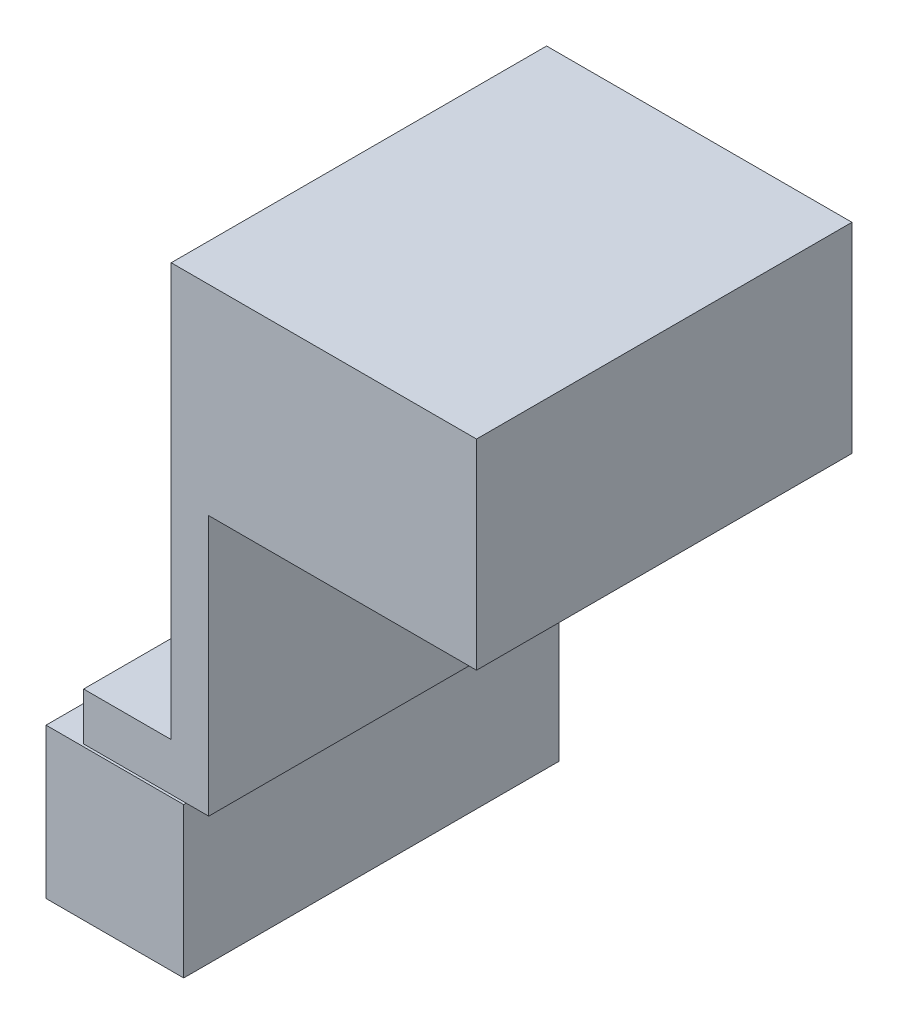
SolidWorks part; units mm, degrees
ref_plane "Front Plane" through (0, 0, 0) normal (0, 0, 1) x (1, 0, 0)
ref_plane "Top Plane" through (0, 0, 0) normal (0, 1, 0) x (1, 0, 0)
ref_plane "Right Plane" through (0, 0, 0) normal (1, 0, 0) x (0, 0, -1)
sketch "Sketch1" plane through (0, 0, 0) normal (0, 0, 1) x (1, 0, 0)
  line L1 (50, 184) -> (157, 184)
  line L2 (50, 184) -> (50, 104)
  line L3 (50, 104) -> (157, 104)
  line L4 (157, 184) -> (157, 104)
  line L5 (-15, -1) -> (40, -1)
  line L6 (-15, -1) -> (-15, -61)
  line L7 (-15, -61) -> (40, -61)
  line L8 (40, -1) -> (40, -61)
  line L9 (0, 0) -> (50, 0)
  line L10 (0, 0) -> (0, 19)
  line L11 (0, 19) -> (50, 19)
  line L12 (50, 0) -> (50, 19)
  line L13 (50, 19) -> (35, 19)
  line L14 (50, 19) -> (50, 184)
  line L15 (50, 184) -> (35, 184)
  line L16 (35, 19) -> (35, 184)
  point P16 (0, 0)
  point P17 (52.6746, 107.5101)
  point P18 (67.2225, 72.9589)
  point P19 (27.822, 125.549)
  dimension "D1" = 19
  dimension "D2" = 50
  dimension "D3" = 184
  dimension "D4" = 35
  dimension "D5" = 104
  dimension "D6" = 157
  dimension "D7" = 1
  dimension "D8" = 15
  dimension "D9" = 40
  dimension "D10" = 60
extrude "Boss-Extrude1" add sketch "Sketch1" along normal blind 150 contours L9 L12 L11 L10 | L16 L11 L14 L2 L15 | L4 L1 L2 L3 | L8 L5 L6 L7
